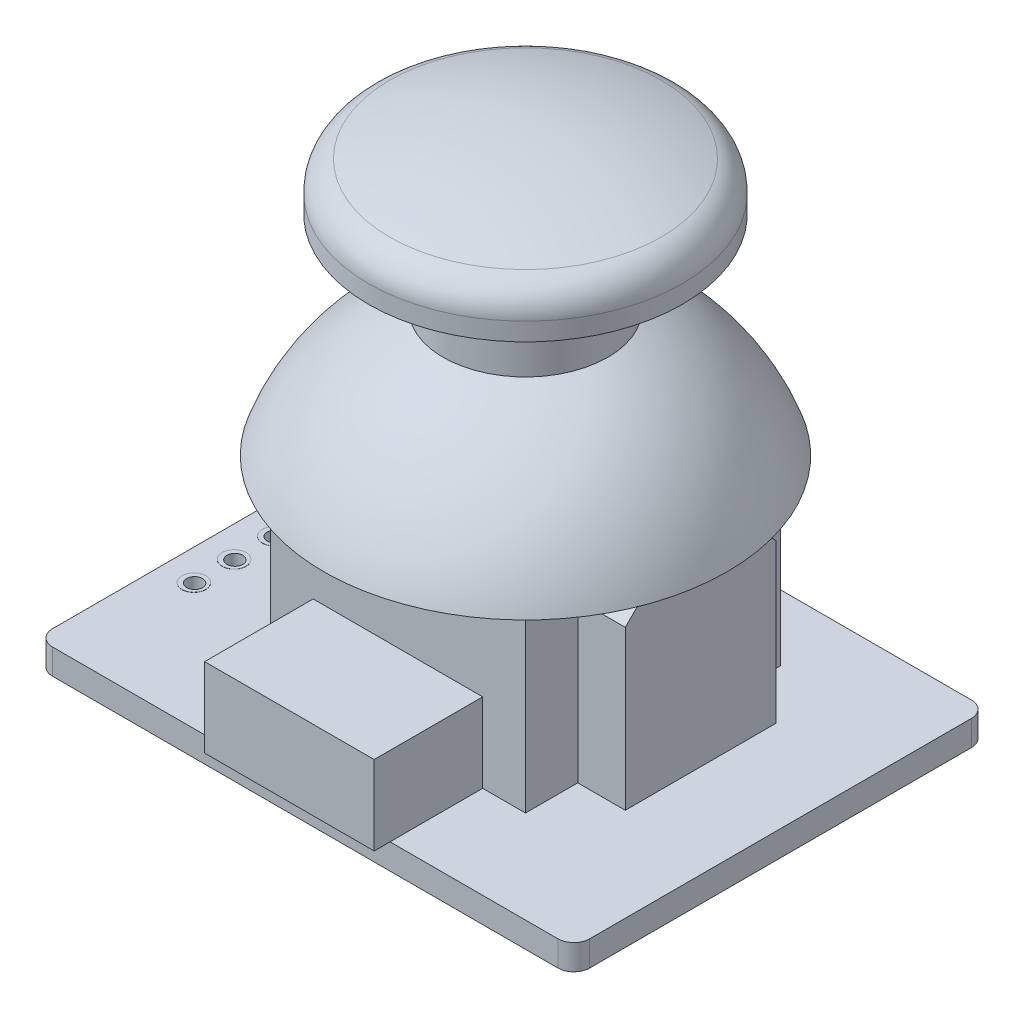
SolidWorks part; units mm, degrees
ref_plane "Front Plane" through (0, 0, 0) normal (0, 0, 1) x (1, 0, 0)
ref_plane "Top Plane" through (0, 0, 0) normal (0, 1, 0) x (1, 0, 0)
ref_plane "Right Plane" through (0, 0, 0) normal (1, 0, 0) x (0, 0, -1)
sketch "Sketch1" plane through (0, 0, 0) normal (0, 1, 0) x (1, 0, 0)
  line L1 (-16.95, 13.05) -> (16.95, 13.05)
  line L2 (-16.95, 13.05) -> (-16.95, -13.05)
  line L3 (-16.95, -13.05) -> (16.95, -13.05)
  line L4 (16.95, 13.05) -> (16.95, -13.05)
  line L5 (0, -13.05) -> (0, 13.05) construction
  line L6 (-16.95, 0) -> (16.95, 0) construction
  point P0 (0, 0)
  dimension "D1" = 26.1
  dimension "D2" = 33.9
extrude "PCB ext" add sketch "Sketch1" along normal blind 1.6
fillet "Fillet1" radius 1 4 edges at (-16.95, 0.8, 13.05) (-16.95, 0.8, -13.05) (16.95, 0.8, -13.05) (16.95, 0.8, 13.05)
sketch "Sketch14" plane through (0, 1.6, 0) normal (0, 1, 0) x (1, 0, 0)
  line L0 (-16.95, 0) -> (16.95, 0) construction
  line L1 (-16.95, 13.05) -> (-16.95, -13.05) construction
  circle A0 centre (-14.95, 0) radius 0.5
  dimension "D1" = 1
  dimension "D2" = 2
extrude "Cut-Extrude1" cut sketch "Sketch14" against normal through all
sketch "Sketch15" plane through (0, 1.6, 0) normal (0, 1, 0) x (1, 0, 0)
  circle A0 centre (-15, 0) radius 0.75
  circle A1 centre (-14.95, 0) radius 0.5 construction
  circle A3 centre (-14.95, 0) radius 0.5
  circle A4 centre (-14.95, 0) radius 0.5
  dimension "D1" = 0.2
  dimension "D2" = 0
extrude "Boss-Extrude6" add sketch "Sketch15" along normal blind 0.01
ref_plane "Plane2" through (0, 0.8, 0) normal (0, 1, 0) x (1, 0, 0)
mirror "Mirror1" about plane through (0, 0.8, 0) normal (0, 1, 0) of "Boss-Extrude6"
pattern_linear "LPattern1" count 3 spacing 2.54 along (0, 0, 1) count 3 spacing 2.54 along (0, 0, -1) of "Cut-Extrude1", "Boss-Extrude6", "Mirror1"
sketch "Sketch2" plane through (0, 1.6, 0) normal (0, 1, 0) x (1, 0, 0)
  line L0 (0, -13.05) -> (0, 13.05) construction
  line L1 (-8.05, 8.9) -> (8.05, 8.9)
  line L2 (-8.05, 8.9) -> (-8.05, -7.2)
  line L3 (-8.05, -7.2) -> (8.05, -7.2)
  line L4 (8.05, 8.9) -> (8.05, -7.2)
  line L5 (-16.95, -13.05) -> (16.95, -13.05) construction
  line L6 (-16.95, 13.05) -> (16.95, 13.05) construction
  line L10 (-8.05, -7.2) -> (8.05, 8.9) construction
  point P0 (0, 0.85)
  point P4 (0, 0.85)
  point P9 (0, 8.9)
  dimension "D1" = 13.9
  dimension "D2" = 12.2
  dimension "D3" = 16.1
extrude "Hat box" add sketch "Sketch2" along normal blind 12 separate body
ref_plane "Hat mox mid pln" through (0, 0, -0.85) normal (0, 0, 1) x (1, 0, 0)
sketch "Sketch10" plane through (0, 1.6, 0) normal (0, 1, 0) x (1, 0, 0)
  line L1 (8.05, -3.9) -> (11.05, -3.9)
  line L2 (8.05, -3.9) -> (8.05, 5.6)
  line L3 (8.05, 5.6) -> (11.05, 5.6)
  line L4 (11.05, -3.9) -> (11.05, 5.6)
  line L5 (8.05, 8.9) -> (8.05, -7.2) construction
  point P7 (8.05, 0.85)
  point P10 (8.05, 0.85)
  dimension "D1" = 3
  dimension "D2" = 9.5
extrude "Boss-Extrude5" add sketch "Sketch10" along normal up to surface (12 mm away) separate body up to face at (0, 13.6, -0.85)
chamfer "Chamfer1" distance 2 angle 45 4 edges at (8.05, 13.6, -0.85) (11.05, 13.6, -0.85) (9.55, 13.6, -5.6) (9.55, 13.6, 3.9)
sketch "Sketch12" plane through (0, 0, -0.85) normal (0, 0, 1) x (1, 0, 0)
  line L0 (0, -998.5) -> (0, 49001.5) construction
pattern_circular "CirPattern1" count 2 every 90 about axis through (0, 0, -0.85) along (0, 1, 0) of bodies 108
sketch "Sketch3" plane through (0, 1.6, 0) normal (0, 1, 0) x (1, 0, 0)
  line L1 (-5.35, -7.2) -> (5.35, -7.2)
  line L2 (-5.35, -7.2) -> (-5.35, -14.05)
  line L3 (-5.35, -14.05) -> (5.35, -14.05)
  line L4 (5.35, -7.2) -> (5.35, -14.05)
  line L7 (-8.05, -7.2) -> (8.05, -7.2) construction
  line L8 (-16.95, -13.05) -> (16.95, -13.05) construction
  point P6 (0, -7.2)
  point P7 (0, -7.2)
  dimension "D1" = 10.7
  dimension "D2" = 1
extrude "Hat push button" add sketch "Sketch3" along normal blind 5
sketch "Sketch4" plane through (0, 13.6, 0) normal (0, 1, 0) x (1, 0, 0)
  circle A0 centre (0, 0.85) radius 2
  dimension "D1" = 4
extrude "Boss-Extrude4" add sketch "Sketch4" along normal blind 7.5
sketch "Sketch9" plane through (0, 0, -0.85) normal (0, 0, 1) x (1, 0, 0)
  line L0 (0, 20.7326) -> (0, 30.8)
  line L1 (-9.9, 30.8) -> (9.9, 30.8) construction
  line L4 (-997.6311, 8.6) -> (49002.3689, 8.6) construction
  line L6 (5.2, 26.3) -> (5.2, 21.0583)
  line L7 (5.2, 26.3) -> (9.9, 26.3)
  line L8 (9.9, 26.3) -> (9.9, 28.8)
  line L9 (-1021.7489, 13.1) -> (48978.2511, 13.1) construction
  line L10 (12.4093, 13.1) -> (12.7279, 13.1)
  line L11 (5.2, 20.7326) -> (0, 20.7326)
  line L13 (0, -961.886) -> (0, 49038.114) construction
  line L14 (0, 20.7326) -> (-5.2, 20.7326) construction
  line L16 (-15.95, 0) -> (15.95, 0) construction
  circle A0 centre (0, 8.6) radius 13.5 construction
  arc A3 (5.2, 21.0583) -> (12.7279, 13.1) centre (0, 8.6) cw
  arc A4 (0, 30.8) -> (9.9, 28.8) centre (0, 5.2975) cw
  arc A5 (5.2, 20.7326) -> (12.4093, 13.1) centre (0, 8.6) cw
  point P19 (0, 30.8)
  dimension "D1" = 27
  dimension "D5" = 2.5
  dimension "D3" = 4.5
  dimension "D9" = 0.3
  dimension "D4" = 10.4
  dimension "D7" = 19.8
  dimension "D8" = 4.5
  dimension "D6" = 30.8
  dimension "D2" = 8.6
revolve "Revolve1" add sketch "Sketch9" angle 360 about L13
fillet "Fillet2" radius 2 1 edges at (0, 28.8, -10.75)
equation "\"D1@Sketch9\"=13.5 * 2"
